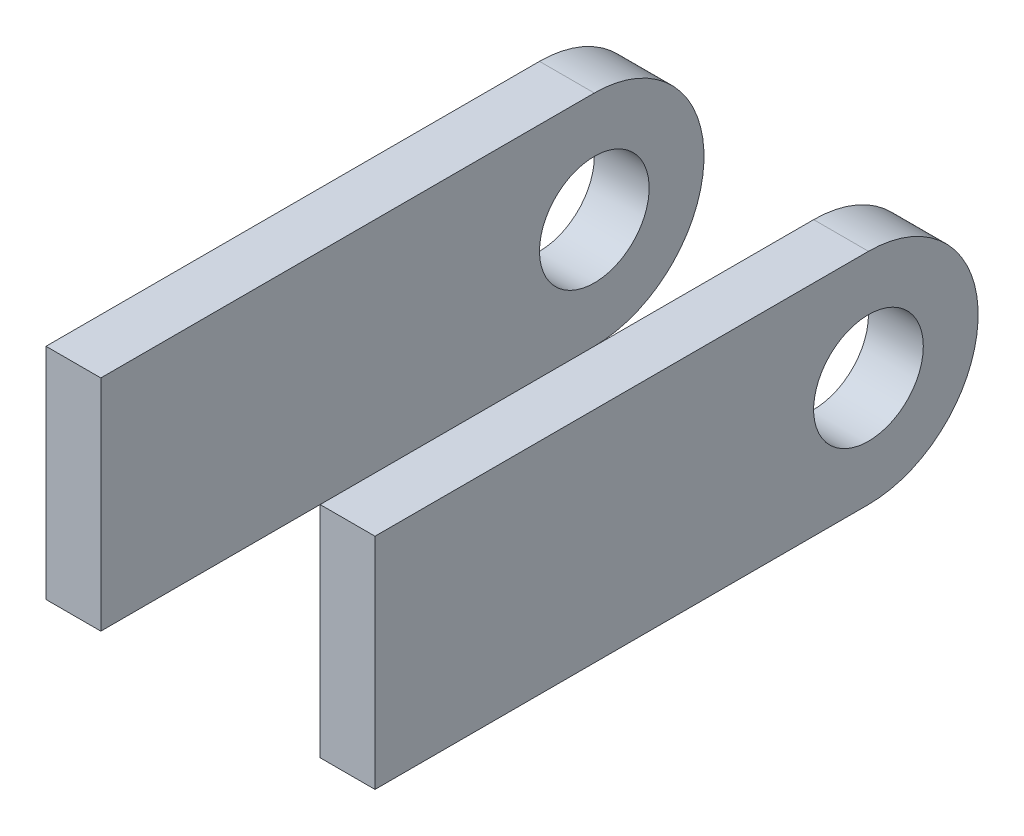
SolidWorks part; units mm, degrees
material "AISI 4130 Steel, normalized at 870C"
ref_plane "Front Plane" through (0, 0, 0) normal (0, 0, 1) x (1, 0, 0)
ref_plane "Top Plane" through (0, 0, 0) normal (0, 1, 0) x (1, 0, 0)
ref_plane "Right Plane" through (0, 0, 0) normal (1, 0, 0) x (0, 0, -1)
sketch "Sketch1" plane through (0, 0, 0) normal (1, 0, 0) x (0, 0, -1)
  line L0 (0, 10) -> (-45, 10)
  line L1 (-45, 10) -> (-45, -10)
  line L2 (-45, -10) -> (0, -10)
  arc A0 (0, -10) -> (0, 10) centre (0, 0) ccw
  circle A1 centre (0, 0) radius 5
  point P6 (0, 0)
  dimension "D1" = 10
  dimension "D2" = 10
  dimension "D3" = 45
extrude "Boss-Extrude1" add sketch "Sketch1" along normal blind 30
sketch "Sketch2" plane through (0, 0, 45) normal (0, 0, 1) x (1, 0, 0)
  line L1 (5, 10) -> (25, 10)
  line L2 (5, 10) -> (5, -10)
  line L3 (5, -10) -> (25, -10)
  line L4 (25, 10) -> (25, -10)
  line L5 (5, 10) -> (25, -10) construction
  line L6 (5, -10) -> (25, 10) construction
  line L7 (30, 10) -> (0, 10) construction
  line L8 (30, -10) -> (0, -10) construction
  point P0 (15, 0)
  point P9 (0, 0)
  point P10 (15, 10)
  dimension "D1" = 20
extrude "Cut-Extrude1" cut sketch "Sketch2" against normal blind 65
